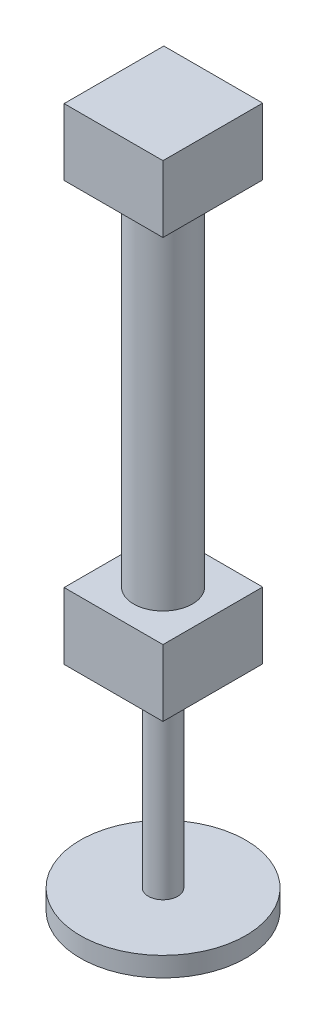
SolidWorks part; units mm, degrees
ref_plane "Front Plane" through (0, 0, 0) normal (0, 0, 1) x (1, 0, 0)
ref_plane "Top Plane" through (0, 0, 0) normal (0, 1, 0) x (1, 0, 0)
ref_plane "Right Plane" through (0, 0, 0) normal (1, 0, 0) x (0, 0, -1)
sketch "Sketch1" plane through (0, 0, 0) normal (0, 1, 0) x (1, 0, 0)
  circle A0 centre (0, 0) radius 15
  dimension "D1" = 30
extrude "Boss-Extrude2" add sketch "Sketch1" along normal blind 194
sketch "Sketch2" plane through (0, 0, 0) normal (0, -1, 0) x (1, 0, 0)
  line L1 (-25.062, -25.4577) -> (25.4137, -25.4577)
  line L2 (-25.062, -25.4577) -> (-25.062, 25.4577)
  line L3 (-25.062, 25.4577) -> (25.4137, 25.4577)
  line L4 (25.4137, -25.4577) -> (25.4137, 25.4577)
extrude "Boss-Extrude3" add sketch "Sketch2" along normal blind 34
ref_plane "Plane1" through (0, 90, 0) normal (0, 1, 0) x (1, 0, 0)
mirror "Mirror1" about plane through (0, 90, 0) normal (0, 1, 0) of "Boss-Extrude3"
sketch "Sketch3" plane through (0, -34, 0) normal (0, -1, 0) x (1, 0, 0)
  circle A0 centre (0, 0) radius 7.5
  dimension "D1" = 15
extrude "Boss-Extrude4" add sketch "Sketch3" along normal blind 99
sketch "Sketch4" plane through (0, 0, 25.4577) normal (0, 0, 1) x (1, 0, 0)
  circle A0 centre (-1.3007, -17.8609) radius 6.5278
  circle A1 centre (0, 196.9149) radius 7.2734
sketch "Sketch5" plane through (0, -133, 0) normal (0, -1, 0) x (1, 0, 0)
  circle A0 centre (0, 0) radius 42.2531
extrude "Boss-Extrude5" add sketch "Sketch5" along normal blind 10
